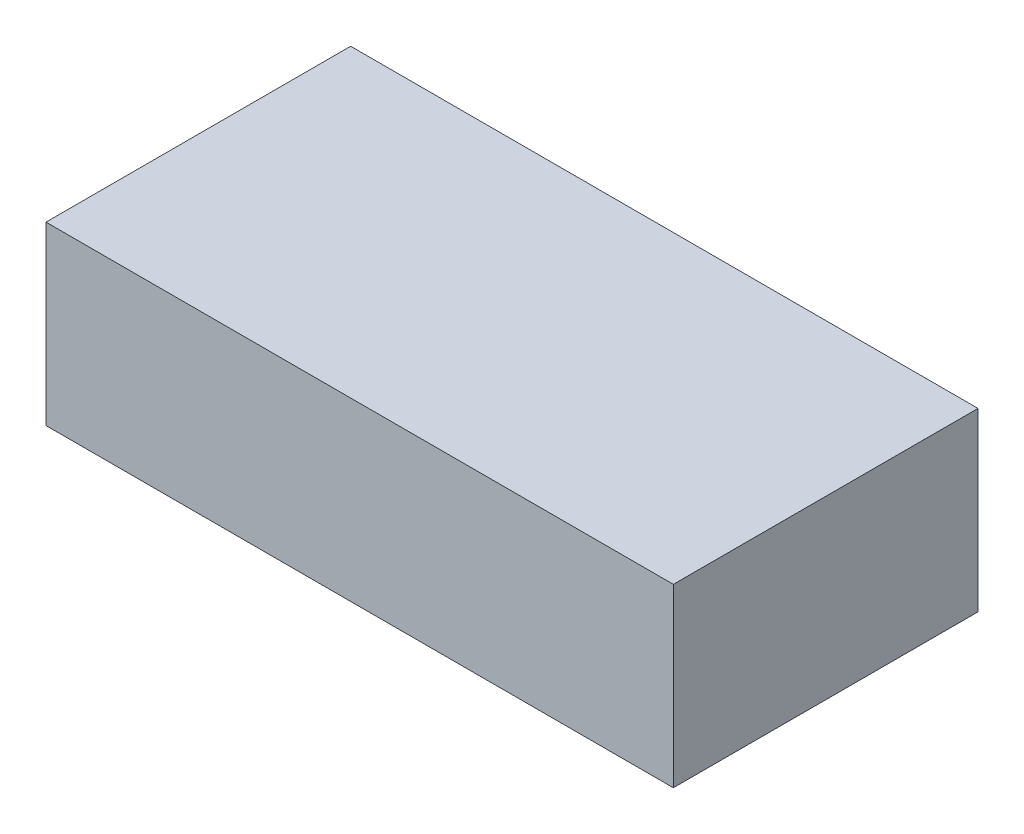
SolidWorks part; units mm, degrees
ref_plane "Front Plane" through (0, 0, 0) normal (0, 0, 1) x (1, 0, 0)
ref_plane "Top Plane" through (0, 0, 0) normal (0, 1, 0) x (1, 0, 0)
ref_plane "Right Plane" through (0, 0, 0) normal (1, 0, 0) x (0, 0, -1)
sketch "Sketch1" plane through (0, 0, 0) normal (0, 1, 0) x (1, 0, 0)
  line L1 (0, 0) -> (47.752, 0)
  line L2 (0, 0) -> (0, 23.1902)
  line L3 (0, 23.1902) -> (47.752, 23.1902)
  line L4 (47.752, 0) -> (47.752, 23.1902)
  dimension "D1" = 47.752
  dimension "D2" = 23.1902
extrude "Boss-Extrude1" add sketch "Sketch1" along normal blind 13.4112
